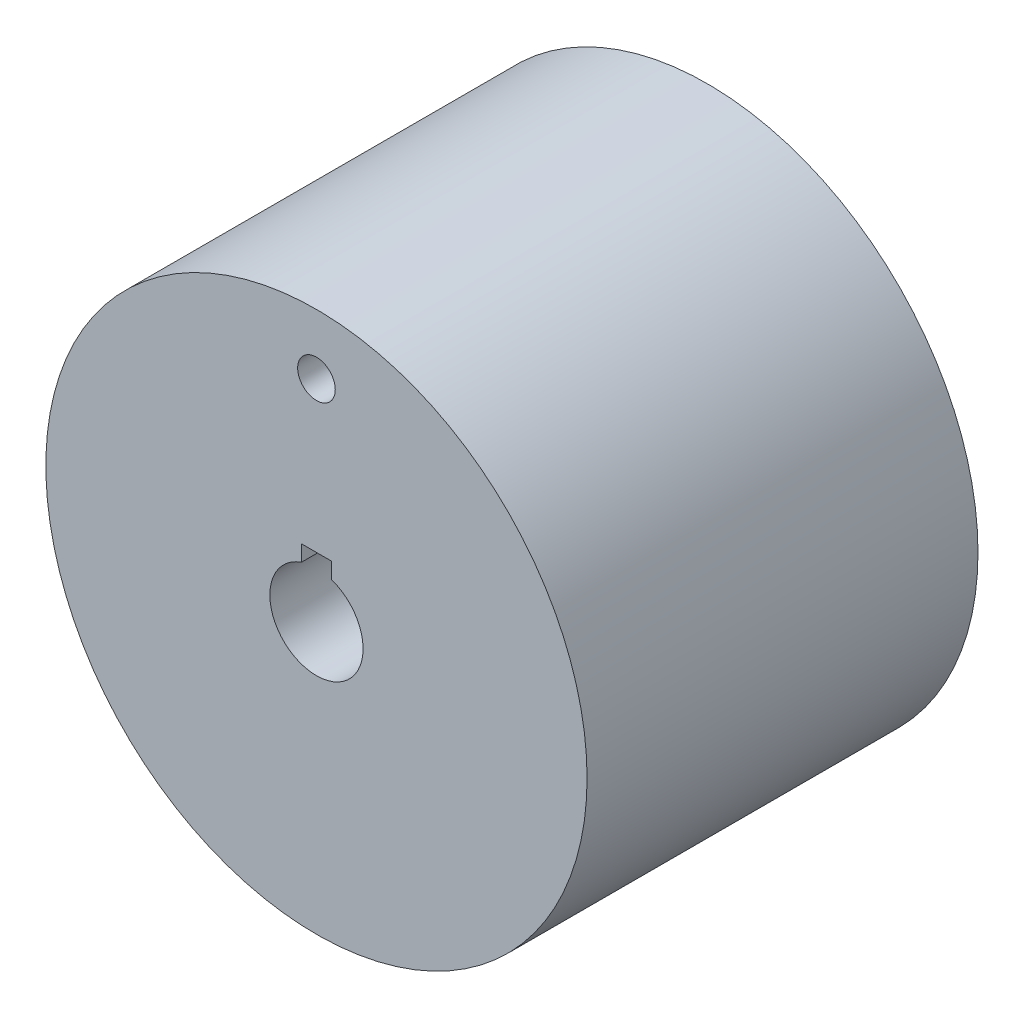
SolidWorks part; units mm, degrees
ref_plane "前视基准面" through (0, 0, 0) normal (0, 0, 1) x (1, 0, 0)
ref_plane "上视基准面" through (0, 0, 0) normal (0, 1, 0) x (1, 0, 0)
ref_plane "右视基准面" through (0, 0, 0) normal (1, 0, 0) x (0, 0, -1)
other "Configuration Table"
sketch "草图1" plane through (0, 0, 0) normal (0, 0, 1) x (1, 0, 0)
  line L0 (-1, 2.9343) -> (-1, 4)
  line L1 (-1, 4) -> (1, 4)
  line L2 (1, 4) -> (1, 2.9343)
  circle A0 centre (0, 0) radius 18
  arc A1 (1, 2.9343) -> (-1, 2.9343) centre (0, 0) cw
  circle A2 centre (0, 14) radius 1.25
extrude "凸台-拉伸1" add sketch "草图1" along normal mid plane 26
